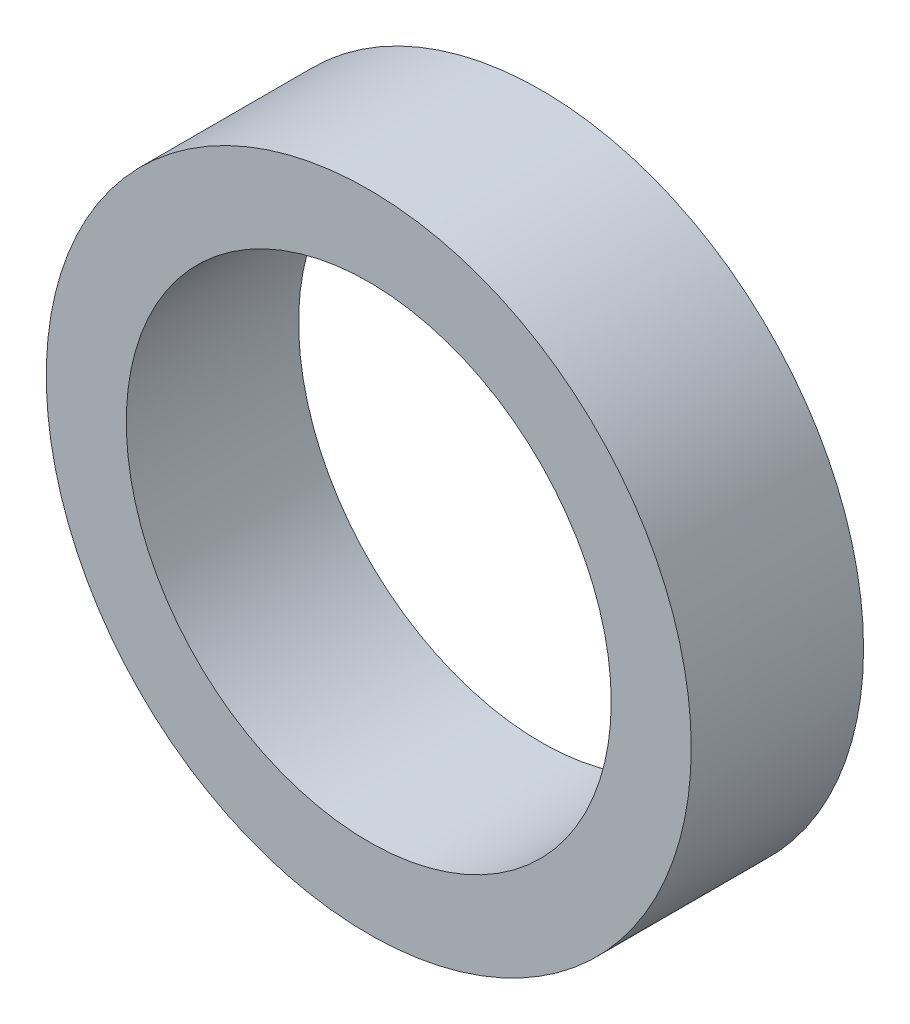
SolidWorks part; units mm, degrees
ref_plane "Alzado" through (0, 0, 0) normal (0, 0, 1) x (1, 0, 0)
ref_plane "Planta" through (0, 0, 0) normal (0, 1, 0) x (1, 0, 0)
ref_plane "Vista lateral" through (0, 0, 0) normal (1, 0, 0) x (0, 0, -1)
sketch "Croquis1" plane through (0, 0, 0) normal (0, 0, 1) x (1, 0, 0)
  circle A0 centre (0, 0) radius 49.25
  circle A1 centre (0, 0) radius 65.5
  dimension "D1" = 98.5
  dimension "D2" = 131
extrude "Saliente-Extruir1" add sketch "Croquis1" along normal blind 35
